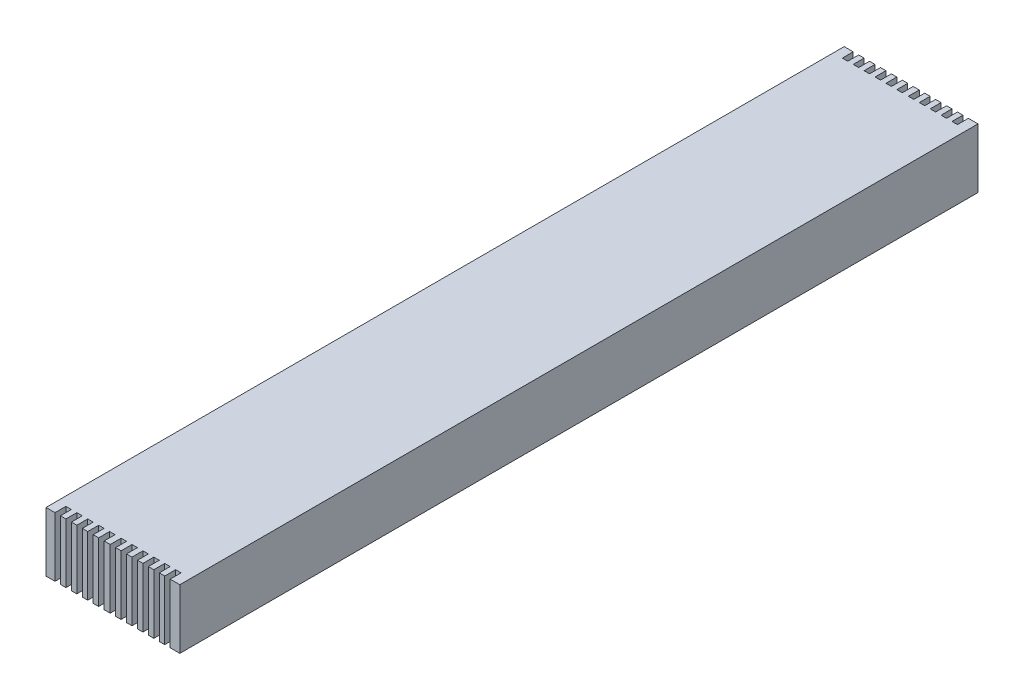
SolidWorks part; units mm, degrees
ref_plane "Front Plane" through (0, 0, 0) normal (0, 0, 1) x (1, 0, 0)
ref_plane "Top Plane" through (0, 0, 0) normal (0, 1, 0) x (1, 0, 0)
ref_plane "Right Plane" through (0, 0, 0) normal (1, 0, 0) x (0, 0, -1)
sketch "Sketch1" plane through (0, 0, 0) normal (0, 0, 1) x (1, 0, 0)
  line L0 (390.2862, -454.0022) -> (340.2862, -454.0022)
  line L1 (-347.891, 41.2406) -> (878.4633, 41.2406)
  line L2 (-347.891, 41.2406) -> (-347.891, -504.0022)
  line L3 (-347.891, -504.0022) -> (-265.3555, -504.0022)
  line L4 (878.4633, 41.2406) -> (878.4633, -504.0022)
  line L5 (340.2862, -454.0022) -> (340.2862, -504.0022)
  line L6 (290.2862, -454.0022) -> (240.2862, -454.0022)
  line L7 (240.2862, -454.0022) -> (240.2862, -504.0022)
  line L8 (290.2862, -454.0022) -> (290.2862, -504.0022)
  line L9 (390.2862, -454.0022) -> (390.2862, -504.0022)
  line L10 (490.2862, -454.0022) -> (440.2862, -454.0022)
  line L11 (440.2862, -454.0022) -> (440.2862, -504.0022)
  line L12 (490.2862, -454.0022) -> (490.2862, -504.0022)
  line L13 (590.2862, -454.0022) -> (540.2862, -454.0022)
  line L14 (540.2862, -454.0022) -> (540.2862, -504.0022)
  line L15 (690.2862, -454.0022) -> (690.2862, -504.0022)
  line L16 (590.2862, -454.0022) -> (590.2862, -504.0022)
  line L17 (690.2862, -454.0022) -> (640.2862, -454.0022)
  line L18 (640.2862, -454.0022) -> (640.2862, -504.0022)
  line L19 (184.6445, -454.0022) -> (134.6445, -454.0022)
  line L20 (790.2862, -454.0022) -> (740.2862, -454.0022)
  line L21 (740.2862, -454.0022) -> (740.2862, -504.0022)
  line L22 (-265.3555, -454.0022) -> (-265.3555, -504.0022)
  line L23 (184.6445, -454.0022) -> (184.6445, -504.0022)
  line L24 (790.2862, -454.0022) -> (790.2862, -504.0022)
  line L25 (84.6445, -454.0022) -> (34.6445, -454.0022)
  line L26 (84.6445, -454.0022) -> (84.6445, -504.0022)
  line L27 (-15.3555, -454.0022) -> (-15.3555, -504.0022)
  line L28 (134.6445, -454.0022) -> (134.6445, -504.0022)
  line L29 (-115.3555, -454.0022) -> (-115.3555, -504.0022)
  line L30 (34.6445, -454.0022) -> (34.6445, -504.0022)
  line L31 (-65.3555, -454.0022) -> (-65.3555, -504.0022)
  line L32 (-215.3555, -454.0022) -> (-265.3555, -454.0022)
  line L33 (-165.3555, -454.0022) -> (-165.3555, -504.0022)
  line L34 (-15.3555, -454.0022) -> (-65.3555, -454.0022)
  line L35 (-115.3555, -454.0022) -> (-165.3555, -454.0022)
  line L36 (-215.3555, -454.0022) -> (-215.3555, -504.0022)
  line L37 (-215.3555, -504.0022) -> (-165.3555, -504.0022)
  line L38 (-115.3555, -504.0022) -> (-65.3555, -504.0022)
  line L39 (-15.3555, -504.0022) -> (34.6445, -504.0022)
  line L40 (84.6445, -504.0022) -> (134.6445, -504.0022)
  line L41 (184.6445, -504.0022) -> (240.2862, -504.0022)
  line L42 (290.2862, -504.0022) -> (340.2862, -504.0022)
  line L43 (390.2862, -504.0022) -> (440.2862, -504.0022)
  line L44 (490.2862, -504.0022) -> (540.2862, -504.0022)
  line L45 (690.2862, -504.0022) -> (740.2862, -504.0022)
  line L46 (790.2862, -504.0022) -> (878.4633, -504.0022)
  line L47 (590.2862, -504.0022) -> (640.2862, -504.0022)
extrude "Boss-Extrude1" add sketch "Sketch1" along normal blind 7315
sketch "Sketch2" plane through (0, 0, 7315) normal (0, 0, 1) x (1, 0, 0)
  line L0 (-265.3555, -454.0022) -> (-265.3555, 201.7073)
  line L1 (-215.3555, 201.7073) -> (-165.3555, 201.7073)
  line L2 (-215.3555, 201.7073) -> (-215.3555, -454.0022)
  line L3 (-215.3555, -454.0022) -> (-265.3555, -454.0022)
  line L4 (-165.3555, 201.7073) -> (-165.3555, -454.0022)
  line L5 (-165.3555, -454.0022) -> (-115.3555, -454.0022)
  line L6 (-115.3555, -454.0022) -> (-115.3555, 201.7073)
  line L7 (-115.3555, 201.7073) -> (-65.3555, 201.7073)
  line L8 (-65.3555, 201.7073) -> (-65.3555, -454.0022)
  line L9 (-65.3555, -454.0022) -> (-15.3555, -454.0022)
  line L10 (-15.3555, -454.0022) -> (-15.3555, 201.7073)
  line L11 (-15.3555, 201.7073) -> (34.6445, 201.7073)
  line L12 (34.6445, 201.7073) -> (34.6445, -454.0022)
  line L13 (34.6445, -454.0022) -> (84.6445, -454.0022)
  line L14 (84.6445, -454.0022) -> (84.6445, 201.7073)
  line L15 (84.6445, 201.7073) -> (134.6445, 201.7073)
  line L16 (134.6445, 201.7073) -> (134.6445, -454.0022)
  line L17 (134.6445, -454.0022) -> (184.6445, -454.0022)
  line L18 (184.6445, -454.0022) -> (184.6445, 201.7073)
  line L19 (184.6445, 201.7073) -> (240.2862, 201.7073)
  line L20 (240.2862, 201.7073) -> (240.2862, -454.0022)
  line L21 (240.2862, -454.0022) -> (290.2862, -454.0022)
  line L22 (290.2862, -454.0022) -> (290.2862, 201.7073)
  line L23 (290.2862, 201.7073) -> (340.2862, 201.7073)
  line L24 (340.2862, 201.7073) -> (340.2862, -454.0022)
  line L25 (340.2862, -454.0022) -> (390.2862, -454.0022)
  line L26 (390.2862, -454.0022) -> (390.2862, 201.7073)
  line L27 (390.2862, 201.7073) -> (440.2862, 201.7073)
  line L28 (440.2862, 201.7073) -> (440.2862, -454.0022)
  line L29 (440.2862, -454.0022) -> (490.2862, -454.0022)
  line L30 (490.2862, -454.0022) -> (490.2862, 201.7073)
  line L31 (490.2862, 201.7073) -> (540.2862, 201.7073)
  line L32 (540.2862, 201.7073) -> (540.2862, -454.0022)
  line L33 (540.2862, -454.0022) -> (590.2862, -454.0022)
  line L34 (590.2862, -454.0022) -> (590.2862, 201.7073)
  line L35 (590.2862, 201.7073) -> (640.2862, 201.7073)
  line L36 (640.2862, 201.7073) -> (640.2862, -454.0022)
  line L37 (640.2862, -454.0022) -> (690.2862, -454.0022)
  line L38 (690.2862, -454.0022) -> (690.2862, 201.7073)
  line L39 (690.2862, 201.7073) -> (740.2862, 201.7073)
  line L40 (740.2862, 201.7073) -> (740.2862, -454.0022)
  line L41 (740.2862, -454.0022) -> (790.2862, -454.0022)
  line L42 (790.2862, -454.0022) -> (790.2862, 367.4342)
  line L43 (790.2862, 367.4342) -> (-265.3555, 367.4342)
  line L44 (-265.3555, 367.4342) -> (-265.3555, 201.7073)
  line L45 (790.2862, -454.0022) -> (1744.499, -200.374) construction
extrude "Cut-Extrude1" cut sketch "Sketch2" against normal blind 100
sketch "Sketch3" plane through (0, 0, 0) normal (0, 0, -1) x (-1, 0, 0)
  line L0 (-790.2862, -454.0022) -> (-790.2862, 201.7073)
  line L1 (-740.2862, 201.7073) -> (-690.2862, 201.7073)
  line L2 (-740.2862, 201.7073) -> (-740.2862, -454.0022)
  line L3 (-740.2862, -454.0022) -> (-790.2862, -454.0022)
  line L4 (-690.2862, 201.7073) -> (-690.2862, -454.0022)
  line L5 (-690.2862, -454.0022) -> (-640.2862, -454.0022)
  line L6 (-640.2862, -454.0022) -> (-640.2862, 201.7073)
  line L7 (-640.2862, 201.7073) -> (-590.2862, 201.7073)
  line L8 (-590.2862, 201.7073) -> (-590.2862, -454.0022)
  line L9 (-590.2862, -454.0022) -> (-540.2862, -454.0022)
  line L10 (-540.2862, -454.0022) -> (-540.2862, 201.7073)
  line L11 (-540.2862, 201.7073) -> (-490.2862, 201.7073)
  line L12 (-490.2862, 201.7073) -> (-490.2862, -454.0022)
  line L13 (-490.2862, -454.0022) -> (-440.2862, -454.0022)
  line L14 (-440.2862, -454.0022) -> (-440.2862, 201.7073)
  line L15 (-440.2862, 201.7073) -> (-390.2862, 201.7073)
  line L16 (-390.2862, 201.7073) -> (-390.2862, -454.0022)
  line L17 (-390.2862, -454.0022) -> (-340.2862, -454.0022)
  line L18 (-340.2862, -454.0022) -> (-340.2862, 201.7073)
  line L19 (-340.2862, 201.7073) -> (-284.6445, 201.7073)
  line L20 (-284.6445, 201.7073) -> (-284.6445, -454.0022)
  line L21 (-284.6445, -454.0022) -> (-234.6445, -454.0022)
  line L22 (-234.6445, -454.0022) -> (-234.6445, 201.7073)
  line L23 (-234.6445, 201.7073) -> (-184.6445, 201.7073)
  line L24 (-184.6445, 201.7073) -> (-184.6445, -454.0022)
  line L25 (-184.6445, -454.0022) -> (-134.6445, -454.0022)
  line L26 (-134.6445, -454.0022) -> (-134.6445, 201.7073)
  line L27 (-134.6445, 201.7073) -> (-84.6445, 201.7073)
  line L28 (-84.6445, 201.7073) -> (-84.6445, -454.0022)
  line L29 (-84.6445, -454.0022) -> (-34.6445, -454.0022)
  line L30 (-34.6445, -454.0022) -> (-34.6445, 201.7073)
  line L31 (-34.6445, 201.7073) -> (15.3555, 201.7073)
  line L32 (15.3555, 201.7073) -> (15.3555, -454.0022)
  line L33 (15.3555, -454.0022) -> (65.3555, -454.0022)
  line L34 (65.3555, -454.0022) -> (65.3555, 201.7073)
  line L35 (65.3555, 201.7073) -> (115.3555, 201.7073)
  line L36 (115.3555, 201.7073) -> (115.3555, -454.0022)
  line L37 (115.3555, -454.0022) -> (165.3555, -454.0022)
  line L38 (165.3555, -454.0022) -> (165.3555, 201.7073)
  line L39 (165.3555, 201.7073) -> (215.3555, 201.7073)
  line L40 (215.3555, 201.7073) -> (215.3555, -454.0022)
  line L41 (215.3555, -454.0022) -> (265.3555, -454.0022)
  line L42 (265.3555, -454.0022) -> (265.3555, 367.4342)
  line L43 (265.3555, 367.4342) -> (-790.2862, 367.4342)
  line L44 (-790.2862, 367.4342) -> (-790.2862, 201.7073)
extrude "Cut-Extrude2" cut sketch "Sketch3" against normal blind 100
